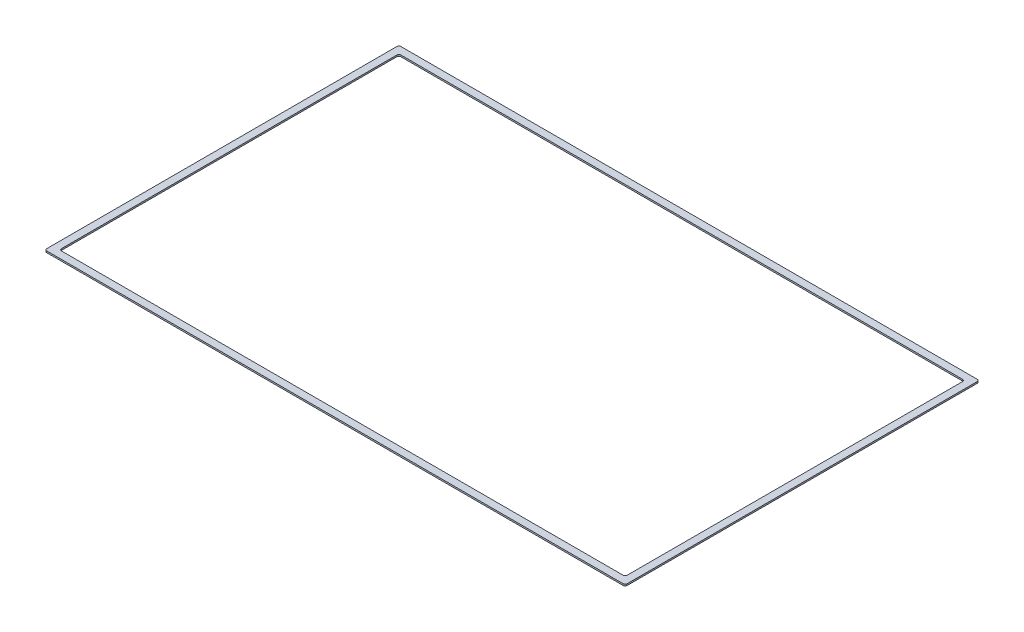
SolidWorks part; units mm, degrees
ref_plane "Front Plane" through (0, 0, 0) normal (0, 0, 1) x (1, 0, 0)
ref_plane "Top Plane" through (0, 0, 0) normal (0, 1, 0) x (1, 0, 0)
ref_plane "Right Plane" through (0, 0, 0) normal (1, 0, 0) x (0, 0, -1)
sketch "Sketch1" plane through (0, 0, 0) normal (0, 1, 0) x (1, 0, 0)
  line L1 (270, -162) -> (-270, -162)
  line L2 (270, -162) -> (270, 162)
  line L3 (270, 162) -> (-270, 162)
  line L4 (-270, -162) -> (-270, 162)
  line L5 (270, -162) -> (-270, 162) construction
  line L6 (270, 162) -> (-270, -162) construction
  line L7 (277, -169) -> (-277, -169)
  line L8 (277, -169) -> (277, 169)
  line L9 (277, 169) -> (-277, 169)
  line L10 (-277, -169) -> (-277, 169)
  line L11 (277, -169) -> (-277, 169) construction
  line L12 (277, 169) -> (-277, -169) construction
  point P0 (0, 0)
  point P6 (0, 0)
  dimension "D1" = 7
  dimension "D2" = 7
  dimension "D3" = 540
  dimension "D4" = 324
extrude "Boss-Extrude1" add sketch "Sketch1" along normal blind 1.5
fillet "Fillet1" radius 2 8 edges at (-270, 0.75, -162) (-277, 0.75, -169) (270, 0.75, -162) (277, 0.75, -169) (270, 0.75, 162) (277, 0.75, 169) (-270, 0.75, 162) (-277, 0.75, 169)
